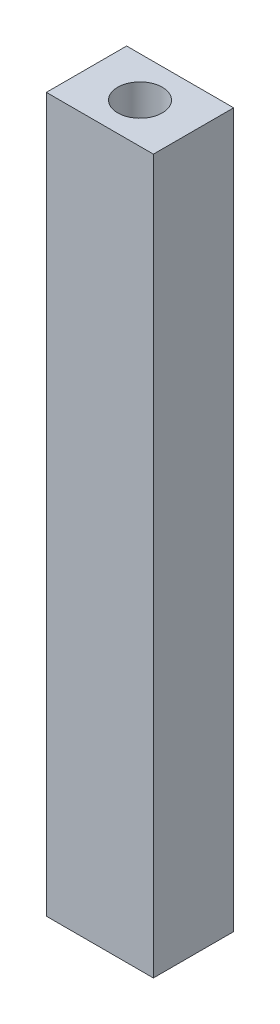
SolidWorks part; units mm, degrees
ref_plane "前视基准面" through (0, 0, 0) normal (0, 0, 1) x (1, 0, 0)
ref_plane "上视基准面" through (0, 0, 0) normal (0, 1, 0) x (1, 0, 0)
ref_plane "右视基准面" through (0, 0, 0) normal (1, 0, 0) x (0, 0, -1)
other "Configuration Table"
sketch "草图2" plane through (0, 0, 0) normal (0, 1, 0) x (1, 0, 0)
  line L1 (-6, -4.5) -> (6, -4.5)
  line L2 (-6, -4.5) -> (-6, 4.5)
  line L3 (-6, 4.5) -> (6, 4.5)
  line L4 (6, -4.5) -> (6, 4.5)
  line L5 (-6, -4.5) -> (6, 4.5) construction
  line L6 (-6, 4.5) -> (6, -4.5) construction
  point P0 (0, 0)
  dimension "D1" = 12
  dimension "D2" = 9
extrude "凸台-拉伸1" add sketch "草图2" along normal blind 80
sketch "草图3" plane through (0, 0, 0) normal (0, -1, 0) x (1, 0, 0)
  circle A0 centre (0, 0) radius 3
  dimension "D1" = 6
extrude "切除-拉伸1" cut sketch "草图3" against normal blind 15
sketch "草图4" plane through (0, 80, 0) normal (0, 1, 0) x (1, 0, 0)
  circle A0 centre (0, 0) radius 2.5
  dimension "D1" = 5
extrude "切除-拉伸2" cut sketch "草图4" against normal blind 15
